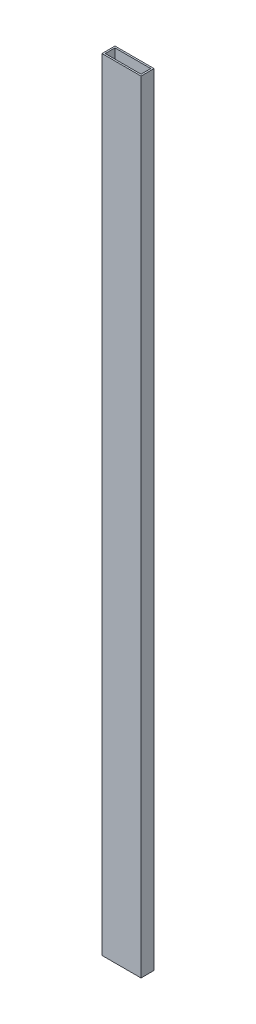
SolidWorks part; units mm, degrees
ref_plane "Front Plane" through (0, 0, 0) normal (0, 0, 1) x (1, 0, 0)
ref_plane "Top Plane" through (0, 0, 0) normal (0, 1, 0) x (1, 0, 0)
ref_plane "Right Plane" through (0, 0, 0) normal (1, 0, 0) x (0, 0, -1)
sketch "Sketch1" plane through (0, 0, 0) normal (0, 1, 0) x (1, 0, 0)
  line L1 (0, 0) -> (-76.2, 0)
  line L2 (0, 0) -> (0, 25.4)
  line L3 (0, 25.4) -> (-76.2, 25.4)
  line L4 (-76.2, 0) -> (-76.2, 25.4)
  line L5 (-73.025, 22.225) -> (-3.175, 22.225)
  line L6 (-73.025, 22.225) -> (-73.025, 3.175)
  line L7 (-73.025, 3.175) -> (-3.175, 3.175)
  line L8 (-3.175, 22.225) -> (-3.175, 3.175)
  dimension "D1" = 76.2
  dimension "D2" = 25.4
  dimension "D3" = 3.175
  dimension "D4" = 3.175
  dimension "D5" = 3.175
  dimension "D6" = 3.175
extrude "Boss-Extrude1" add sketch "Sketch1" along normal blind 1524
